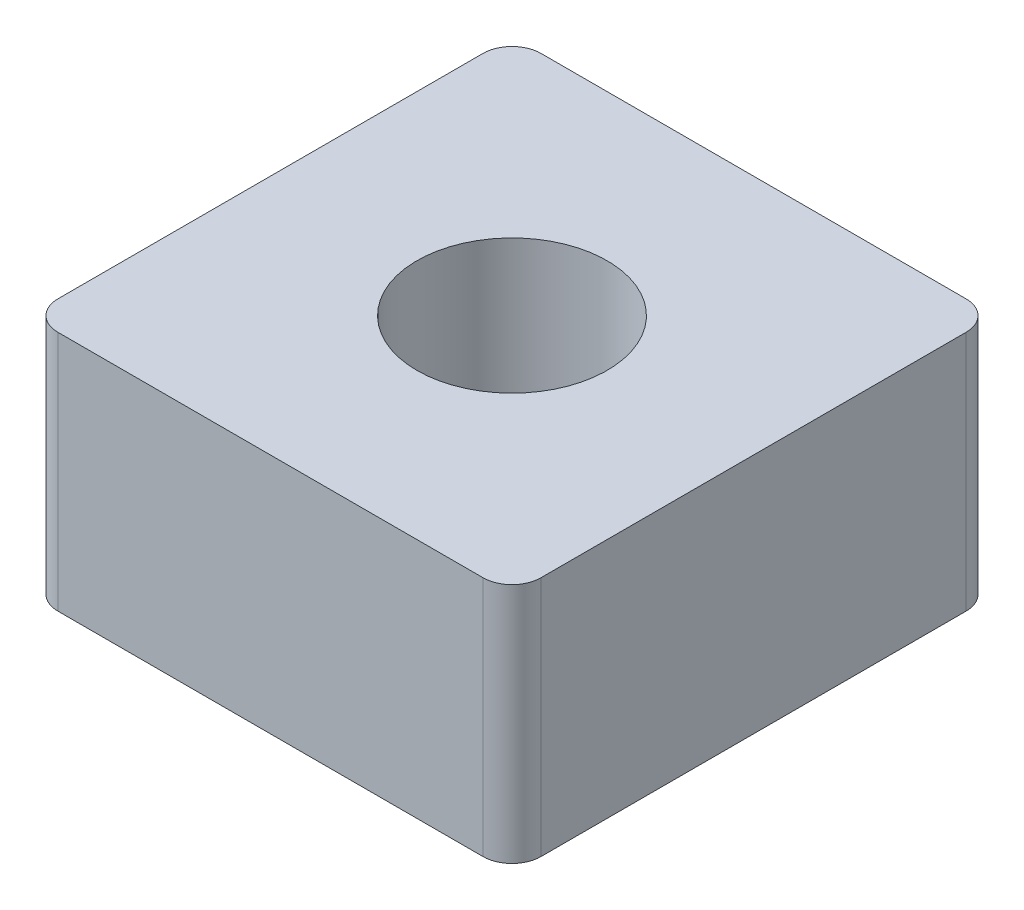
SolidWorks part; units mm, degrees
material "Plain Carbon Steel"
ref_plane "Front Plane" through (0, 0, 0) normal (0, 0, 1) x (1, 0, 0)
ref_plane "Top Plane" through (0, 0, 0) normal (0, 1, 0) x (1, 0, 0)
ref_plane "Right Plane" through (0, 0, 0) normal (1, 0, 0) x (0, 0, -1)
sketch "Sketch1" plane through (0, 0, 0) normal (0, 1, 0) x (1, 0, 0)
  line L1 (-5.588, -6.35) -> (5.588, -6.35)
  line L2 (-6.35, -5.588) -> (-6.35, 5.588)
  line L3 (-5.588, 6.35) -> (5.588, 6.35)
  line L4 (6.35, -5.588) -> (6.35, 5.588)
  line L5 (0, 6.35) -> (0, -6.35) construction
  line L6 (-6.35, 0) -> (6.35, 0) construction
  arc A0 (-5.588, -6.35) -> (-6.35, -5.588) centre (-5.588, -5.588) cw
  arc A1 (5.588, -6.35) -> (6.35, -5.588) centre (5.588, -5.588) ccw
  arc A2 (5.588, 6.35) -> (6.35, 5.588) centre (5.588, 5.588) cw
  arc A3 (-6.35, 5.588) -> (-5.588, 6.35) centre (-5.588, 5.588) cw
  point P0 (0, 0)
  point P8 (6.35, -6.35)
  point P12 (6.35, 6.35)
  dimension "D2" = 0.762
  dimension "D1" = 12.7
extrude "Boss-Extrude1" add sketch "Sketch1" along normal blind 6.35
sketch "Sketch4" plane through (0, 6.35, 0) normal (0, 1, 0) x (1, 0, 0)
  point P0 (0, 0)
hole_wizard "M6x1.0 Tapped Hole1" positions "Sketch4" profile "Sketch3" tap size "M6x1.0" standard "ANSI Metric" end condition through all
sketch "Sketch3" plane through (0, 6.35, 0) normal (1, 0, 0) x (0, 0, 1)
  line L0 (0, 0) -> (0, 6.35)
  line L1 (0, 6.35) -> (2.5, 6.35)
  line L2 (2.5, 6.35) -> (2.5, 0)
  line L5 (2.5, 0) -> (0, 0)
  line L11 (0, -6.35) -> (0, 107.95) construction
  dimension "Thru Tap Drill Dia." = 5
  dimension "Thru Tap Drill Depth" = 6.35
cosmetic thread "Hole Thread1" parameters "D2"=6
